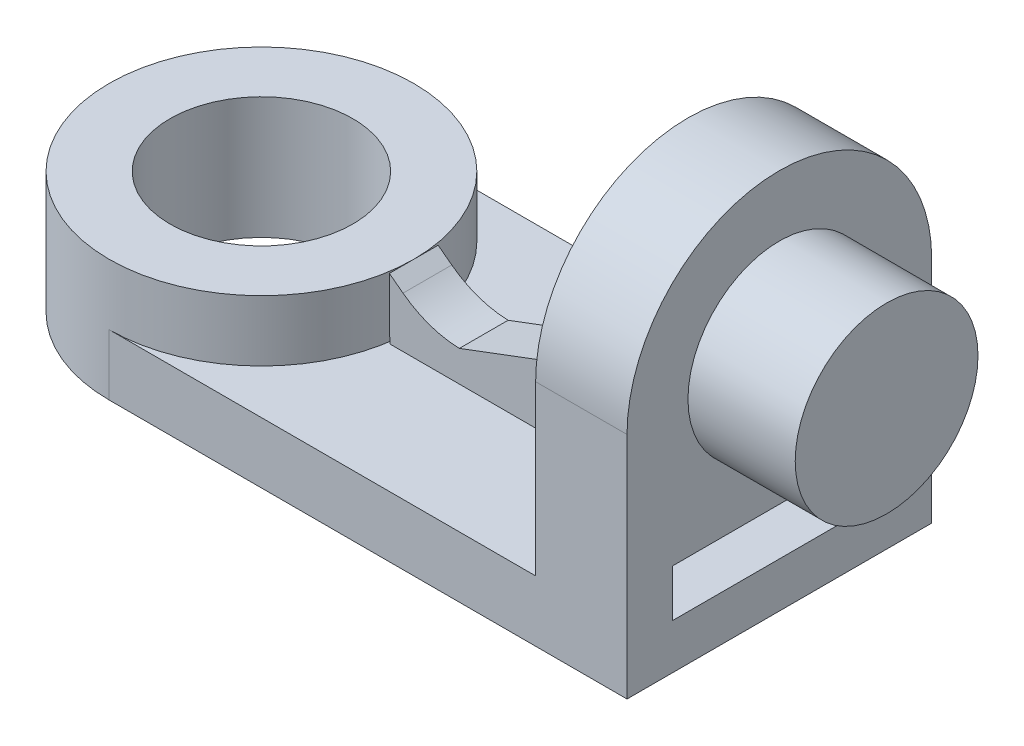
SolidWorks part; units mm, degrees
material "Alloy Steel"
ref_plane "Front Plane" through (0, 0, 0) normal (0, 0, 1) x (1, 0, 0)
ref_plane "Top Plane" through (0, 0, 0) normal (0, 1, 0) x (1, 0, 0)
ref_plane "Right Plane" through (0, 0, 0) normal (1, 0, 0) x (0, 0, -1)
sketch "Sketch1" plane through (0, 0, 0) normal (0, 1, 0) x (1, 0, 0)
  line L1 (0, 0) -> (53.975, 0)
  line L2 (0, 0) -> (0, -31.75)
  line L3 (0, -31.75) -> (53.975, -31.75)
  line L4 (53.975, 0) -> (53.975, -31.75)
  dimension "D1" = 31.75
  dimension "D2" = 53.975
extrude "Boss-Extrude1" add sketch "Sketch1" along normal blind 6.35
sketch "Sketch2" plane through (0, 0, 0) normal (0, 1, 0) x (1, 0, 0)
  line L0 (0, 0) -> (0, -31.75) construction
  circle A0 centre (0, -15.875) radius 15.875
  dimension "D1" = 31.75
extrude "Boss-Extrude2" add sketch "Sketch2" along normal blind 12.7
sketch "Sketch3" plane through (0, 12.7, 0) normal (0, 1, 0) x (1, 0, 0)
  circle A0 centre (0, -15.875) radius 9.525
  dimension "D1" = 19.05
extrude "Cut-Extrude1" cut sketch "Sketch3" against normal blind 12.7
sketch "Sketch4" plane through (0, 6.35, 0) normal (0, 1, 0) x (1, 0, 0)
  line L0 (0, -31.75) -> (53.975, -31.75) construction
  line L1 (53.975, 0) -> (44.45, 0)
  line L2 (53.975, 0) -> (53.975, -31.75)
  line L3 (53.975, -31.75) -> (44.45, -31.75)
  line L4 (44.45, 0) -> (44.45, -31.75)
  dimension "D1" = 9.525
extrude "Boss-Extrude4" add sketch "Sketch4" along normal blind 17.526
sketch "Sketch6" plane through (53.975, 0, 0) normal (1, 0, 0) x (0, 0, -1)
  line L0 (-31.75, 23.876) -> (0, 23.876) construction
  circle A0 centre (-15.875, 23.876) radius 15.875
extrude "Boss-Extrude5" add sketch "Sketch6" against normal blind 9.525
sketch "Sketch7" plane through (53.975, 0, 0) normal (1, 0, 0) x (0, 0, -1)
  circle A0 centre (-15.875, 23.876) radius 9.525
  dimension "D1" = 19.05
extrude "Boss-Extrude6" add sketch "Sketch7" along normal blind 11.176
sketch "Sketch8" plane through (0, 6.35, 0) normal (0, 1, 0) x (1, 0, 0)
  line L0 (15.875, -15.875) -> (44.45, -15.875) construction
  line L1 (44.45, 0) -> (44.45, -31.75) construction
  arc A0 (0, -31.75) -> (0, 0) centre (0, -15.875) ccw construction
  point P8 (0, 0)
sketch3d "3DSketch1"
  line L0 (15.947, 1.7106, 15.875) -> (44.3323, 2.0473, 15.875)
  line L4 (44.3323, 2.0473, 15.875) -> (44.3323, 17.5413, 15.875)
  line L7 (17.2967, 11.6261, 15.875) -> (15.875, 12.7, 15.875)
  line L8 (15.875, 12.7, 15.875) -> (15.947, 1.7106, 15.875)
  line L9 (44.3323, 17.5413, 15.875) -> (23.1696, 9.5764, 15.875)
  circle A0 centre (0, 12.7, 15.875) radius 15.875 construction
  arc A1 (23.1696, 9.5764, 15.875) -> (17.2967, 11.6261, 15.875) centre (23.4204, 19.7333, 15.875) ccw
  point P3 (0, 0, 0)
  point P8 (0, 28.575, 15.875)
  point P9 (44.6772, 23.3155, 15.875)
  point P10 (44.3323, 17.5413, 15.875)
  point P15 (20.0144, 9.5733, 15.875)
  point P16 (23.4204, 19.7333, 5.715)
  dimension "D2" = 10.16
  dimension "D1" = 15.875
  dimension "D3" = 19.945
  dimension "D4" = 15.494
extrude "Boss-Extrude11" add sketch "3DSketch1" along direction (0, 0, 1) on the side of the normal blind 2.54 and the other way blind 2.54 separate body contours L9 A1 L7 L8 L0 L4
sketch "Sketch10" plane through (53.975, 0, 0) normal (1, 0, 0) x (0, 0, -1)
  line L0 (-15.875, 0) -> (-15.875, 14.351) construction
  line L1 (-31.75, 0) -> (0, 0) construction
  line L3 (-26.995, 4.7102) -> (-4.755, 4.7102)
  line L4 (-26.995, 4.7102) -> (-26.995, 9.6408)
  line L5 (-26.995, 9.6408) -> (-4.755, 9.6408)
  line L6 (-4.755, 4.7102) -> (-4.755, 9.6408)
  line L7 (-26.995, 4.7102) -> (-4.755, 9.6408) construction
  line L8 (-26.995, 9.6408) -> (-4.755, 4.7102) construction
  circle A0 centre (-15.875, 23.876) radius 9.525 construction
  point P7 (-15.875, 7.1755)
extrude "Cut-Extrude2" cut sketch "Sketch10" against normal blind 7.62
